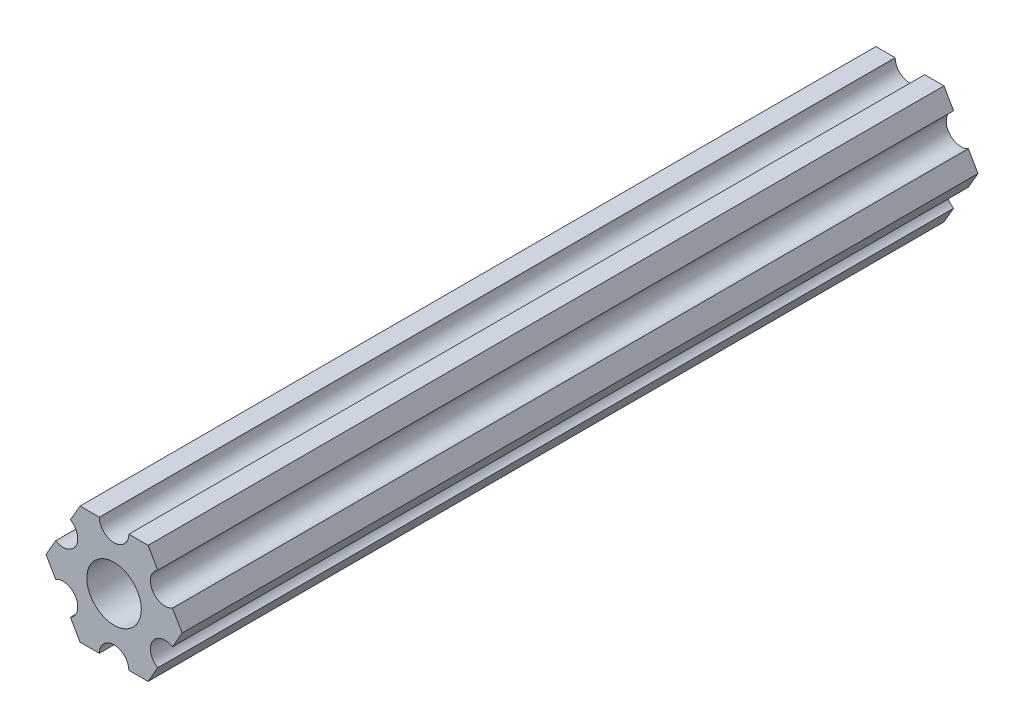
SolidWorks part; units mm, degrees
ref_plane "Front Plane" through (0, 0, 0) normal (0, 0, 1) x (1, 0, 0)
ref_plane "Top Plane" through (0, 0, 0) normal (0, 1, 0) x (1, 0, 0)
ref_plane "Right Plane" through (0, 0, 0) normal (1, 0, 0) x (0, 0, -1)
ref_plane "Plane1" through (0, 0, 0) normal (0, 0, -1) x (-1, 0, 0)
sketch "Sketch1" plane through (0, 0, 0) normal (0, 0, -1) x (-1, 0, 0)
  line L0 (-4.7055, -4.5498) -> (-3.6662, -6.35)
  line L1 (-3.6662, -6.35) -> (-1.5875, -6.35)
  line L2 (1.5875, -6.35) -> (3.6662, -6.35)
  line L3 (3.6662, -6.35) -> (4.7055, -4.5498)
  line L4 (6.293, -1.8002) -> (7.3323, 0)
  line L5 (7.3323, 0) -> (6.293, 1.8002)
  line L6 (4.7055, 4.5498) -> (3.6662, 6.35)
  line L7 (3.6662, 6.35) -> (1.5875, 6.35)
  line L8 (-1.5875, 6.35) -> (-3.6662, 6.35)
  line L9 (-3.6662, 6.35) -> (-4.7055, 4.5498)
  line L10 (-6.293, 1.8002) -> (-7.3323, 0)
  line L11 (-7.3323, 0) -> (-6.293, -1.8002)
  circle A0 centre (0, 0) radius 2.9337
  arc A1 (-6.293, -1.8002) -> (-4.7055, -4.5498) centre (-5.4993, -3.175) cw
  arc A2 (-1.5875, -6.35) -> (1.5875, -6.35) centre (0, -6.35) cw
  arc A3 (4.7055, -4.5498) -> (6.293, -1.8002) centre (5.4993, -3.175) cw
  arc A4 (6.293, 1.8002) -> (4.7055, 4.5498) centre (5.4993, 3.175) cw
  arc A5 (1.5875, 6.35) -> (-1.5875, 6.35) centre (0, 6.35) cw
  arc A6 (-4.7055, 4.5498) -> (-6.293, 1.8002) centre (-5.4993, 3.175) cw
extrude "Boss-Extrude1" add sketch "Sketch1" against normal blind 85.725
